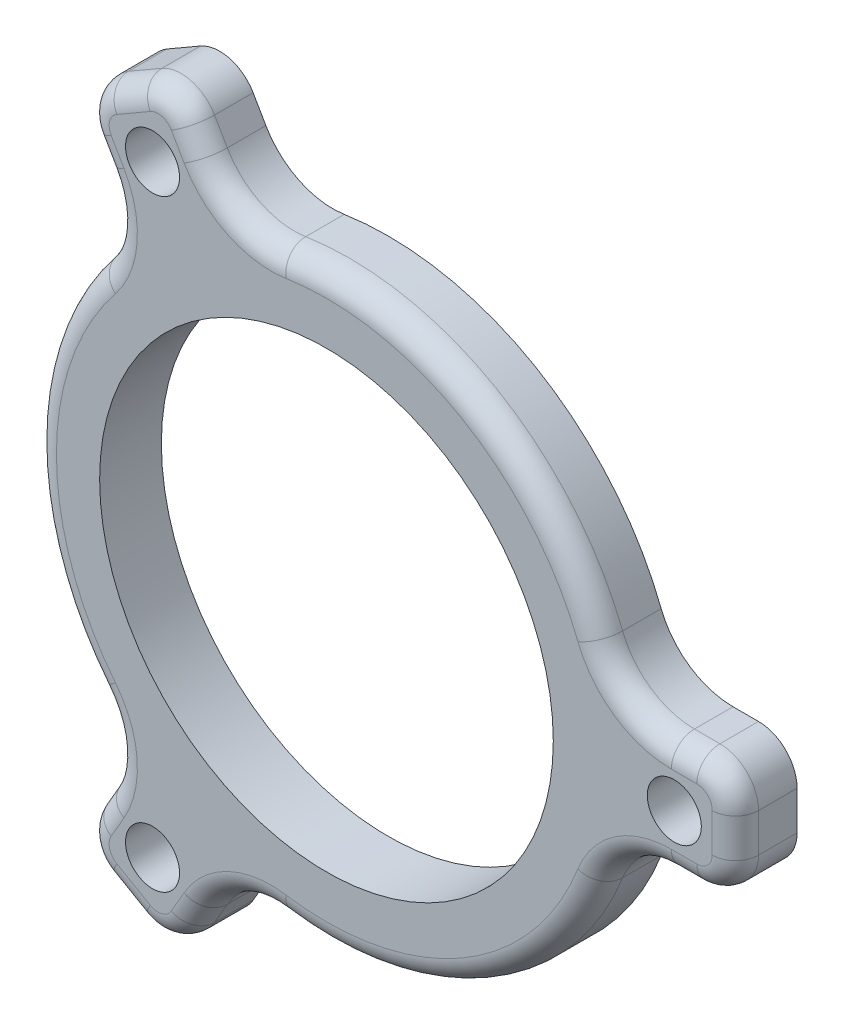
SolidWorks part; units mm, degrees
ref_plane "Front Plane" through (0, 0, 0) normal (0, 0, 1) x (1, 0, 0)
ref_plane "Top Plane" through (0, 0, 0) normal (0, 1, 0) x (1, 0, 0)
ref_plane "Right Plane" through (0, 0, 0) normal (1, 0, 0) x (0, 0, -1)
sketch "Sketch1" plane through (0, 0, 0) normal (0, 0, 1) x (1, 0, 0)
  line L11 (-34.3502, 16.25) -> (-29.8653, 16.25)
  line L12 (-29.8653, -16.25) -> (-34.3502, -16.25)
  line L13 (-28.8433, -34.958) -> (-30.4952, -37.8192)
  line L14 (-28.6651, -44.6493) -> (-24.3349, -47.1493)
  line L15 (-17.5048, -45.3192) -> (-15.8529, -42.458)
  line L16 (44.6962, -7.5) -> (48, -7.5)
  line L17 (53, -2.5) -> (53, 2.5)
  line L18 (48, 7.5) -> (44.6962, 7.5)
  line L19 (-15.8529, 42.458) -> (-17.5048, 45.3192)
  line L20 (-24.3349, 47.1493) -> (-28.6651, 44.6493)
  line L21 (-30.4952, 37.8192) -> (-28.8433, 34.958)
  line L24 (-28.8433, -34.958) -> (-30.4952, -37.8192)
  line L25 (-28.6651, -44.6493) -> (-24.3349, -47.1493)
  line L26 (-17.5048, -45.3192) -> (-15.8529, -42.458)
  line L27 (44.6962, -7.5) -> (48, -7.5)
  line L28 (53, -2.5) -> (53, 2.5)
  line L29 (48, 7.5) -> (44.6962, 7.5)
  line L30 (-15.8529, 42.458) -> (-17.5048, 45.3192)
  line L31 (-24.3349, 47.1493) -> (-28.6651, 44.6493)
  line L32 (-30.4952, 37.8192) -> (-28.8433, 34.958)
  circle A0 centre (45.0848, 0) radius 2.217 construction
  circle A1 centre (-22.5424, -39.0445) radius 2.217 construction
  circle A2 centre (-22.5424, 39.0445) radius 2.217 construction
  circle A3 centre (45.0848, 0) radius 2.217 construction
  circle A4 centre (-22.5424, -39.0445) radius 2.217 construction
  circle A5 centre (-22.5424, 39.0445) radius 2.217 construction
  circle A6 centre (0, 0) radius 29.4 construction
  circle A7 centre (0, 0) radius 29.4
  arc A11 (-29.8653, -16.25) -> (-29.8653, 16.25) centre (0, 0) ccw
  arc A12 (-34.3502, -16.25) -> (-29.6903, -23.7168) centre (0, 0) ccw
  arc A13 (-30.4952, -37.8192) -> (-28.6651, -44.6493) centre (-26.1651, -40.3192) ccw
  arc A14 (-24.3349, -47.1493) -> (-17.5048, -45.3192) centre (-21.8349, -42.8192) ccw
  arc A15 (-28.8433, -34.958) -> (-29.6903, -23.7168) centre (-37.5035, -29.958) ccw
  arc A16 (48, -7.5) -> (53, -2.5) centre (48, -2.5) ccw
  arc A17 (53, 2.5) -> (48, 7.5) centre (48, 2.5) ccw
  arc A18 (-28.8433, -34.958) -> (-29.6903, -23.7168) centre (-37.5035, -29.958) ccw
  arc A19 (-17.5048, 45.3192) -> (-24.3349, 47.1493) centre (-21.8349, 42.8192) ccw
  arc A20 (-28.6651, 44.6493) -> (-30.4952, 37.8192) centre (-26.1651, 40.3192) ccw
  arc A21 (-29.6903, 23.7168) -> (-34.3502, 16.25) centre (0, 0) ccw
  arc A23 (-34.3502, 16.25) -> (-29.6903, -23.7168) centre (0, 0) ccw
  arc A24 (-30.4952, -37.8192) -> (-28.6651, -44.6493) centre (-26.1651, -40.3192) ccw
  arc A25 (-24.3349, -47.1493) -> (-17.5048, -45.3192) centre (-21.8349, -42.8192) ccw
  arc A27 (48, -7.5) -> (53, -2.5) centre (48, -2.5) ccw
  arc A28 (53, 2.5) -> (48, 7.5) centre (48, 2.5) ccw
  arc A30 (-17.5048, 45.3192) -> (-24.3349, 47.1493) centre (-21.8349, 42.8192) ccw
  arc A31 (-28.6651, 44.6493) -> (-30.4952, 37.8192) centre (-26.1651, 40.3192) ccw
  arc A32 (-29.6903, 23.7168) -> (-34.3502, 16.25) centre (0, 0) ccw
  circle A53 centre (45.0848, 0) radius 3.5
  circle A54 centre (-22.5424, -39.0445) radius 3.5
  circle A55 centre (-22.5424, 39.0445) radius 3.5
  arc A67 (-5.6942, -37.5709) -> (-15.8529, -42.458) centre (-7.1927, -47.458) ccw
  arc A68 (-5.6942, -37.5709) -> (-15.8529, -42.458) centre (-7.1927, -47.458) ccw
  arc A69 (-5.6942, -37.5709) -> (35.3845, -13.8542) centre (0, 0) ccw
  arc A70 (-5.6942, -37.5709) -> (35.3845, -13.8542) centre (0, 0) ccw
  arc A71 (44.6962, -7.5) -> (35.3845, -13.8542) centre (44.6962, -17.5) ccw
  arc A72 (44.6962, -7.5) -> (35.3845, -13.8542) centre (44.6962, -17.5) ccw
  arc A73 (35.3845, 13.8542) -> (44.6962, 7.5) centre (44.6962, 17.5) ccw
  arc A74 (35.3845, 13.8542) -> (44.6962, 7.5) centre (44.6962, 17.5) ccw
  arc A75 (35.3845, 13.8542) -> (-5.6942, 37.5709) centre (0, 0) ccw
  arc A76 (35.3845, 13.8542) -> (-5.6942, 37.5709) centre (0, 0) ccw
  arc A77 (-15.8529, 42.458) -> (-5.6942, 37.5709) centre (-7.1927, 47.458) ccw
  arc A78 (-15.8529, 42.458) -> (-5.6942, 37.5709) centre (-7.1927, 47.458) ccw
  arc A79 (-29.6903, 23.7168) -> (-28.8433, 34.958) centre (-37.5035, 29.958) ccw
  arc A80 (-29.6903, 23.7168) -> (-28.8433, 34.958) centre (-37.5035, 29.958) ccw
  dimension "D2" = 7
  dimension "D3" = 7
  dimension "D4" = 7
  dimension "D1" = 0
extrude "Boss-Extrude1" add sketch "Sketch1" along normal blind 8 contours L30 A30 L31 A31 L32 A32 A7 A23 L24 A24 L25 A25 L26 L27 A27 L28 A28 L29
fillet "Fillet1" radius 3 24 edges at (-29.6692, -36.3886, 8) (-16.6789, -43.8886, 8) (-20.5408, -47.6488, 8) (-26.5, -45.8993, 8) (46.3481, 7.5, 8) (51.5355, 6.0355, 8) (53, 0, 8) (51.5355, -6.0355, 8) (-16.6789, 43.8886, 8) (-20.5408, 47.6488, 8) (-26.5, 45.8993, 8) (-30.9947, 41.6133, 8) (-30.9947, -41.6133, 8) (46.3481, -7.5, 8) (-29.6692, 36.3886, 8) (-38, 0, 8) (-27.5318, 29.2067, 8) (-11.5278, 38.4466, 8) (19, 32.909, 8) (39.0596, 9.2399, 8) (39.0596, -9.2399, 8) (19, -32.909, 8) (-11.5278, -38.4466, 8) (-27.5318, -29.2067, 8)
equation "\"D3@Sketch1\"=\"D2@Sketch1\""
equation "\"D4@Sketch1\"=\"D2@Sketch1\""
